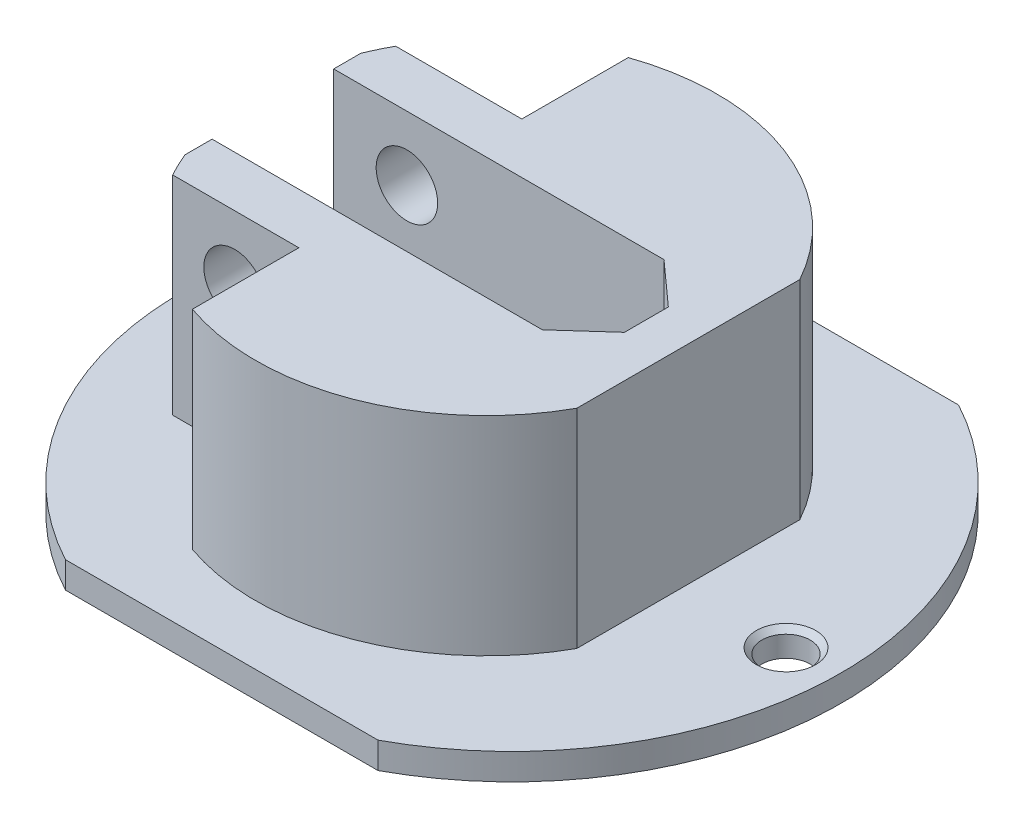
SolidWorks part; units mm, degrees
ref_plane "Front Plane" through (0, 0, 0) normal (0, 0, 1) x (1, 0, 0)
ref_plane "Top Plane" through (0, 0, 0) normal (0, 1, 0) x (1, 0, 0)
ref_plane "Right Plane" through (0, 0, 0) normal (1, 0, 0) x (0, 0, -1)
sketch "Sketch1" plane through (0, 0, 0) normal (0, 1, 0) x (1, 0, 0)
  line L0 (0, 0) -> (12.8, 0)
  line L1 (12.8, 0) -> (15.6935, -2.6)
  line L2 (15.6935, -2.6) -> (15.6935, -5.6)
  line L3 (15.6935, -5.6) -> (12.8, -8.2)
  line L4 (12.8, -8.2) -> (0, -8.2)
  line L5 (0, -8.2) -> (0, 0)
  dimension "D1" = 12.8
  dimension "D2" = 3.89
  dimension "D3" = 3
  dimension "D4" = 3.89
  dimension "D5" = 8.2
sketch "Sketch2" plane through (0, 0, 0) normal (0, 1, 0) x (1, 0, 0)
  line L9 (2.5617, 3.5098) -> (-4.4383, 3.5098)
  line L13 (-4.4383, -11.7098) -> (2.5617, -11.7098)
  line L21 (15.7777, 0.05) -> (-5.3065, 0.05)
  line L22 (0, 0) -> (12.8, 0) construction
  line L24 (15.7777, -8.25) -> (-5.3065, -8.25)
  line L25 (12.8, -8.2) -> (0, -8.2) construction
  line L27 (18.6713, -2.5999) -> (18.6713, -5.5999)
  line L28 (18.6713, -5.5999) -> (15.7777, -8.1998)
  line L30 (18.6713, -2.5999) -> (15.7777, 0)
  line L36 (2.5617, 3.5098) -> (2.5617, 9.296)
  line L37 (2.5617, -11.7098) -> (2.5617, -17.496)
  line L39 (15.7777, -8.1998) -> (15.7777, -8.25)
  line L40 (15.7777, 0.05) -> (15.7777, 0)
  line L41 (2.5617, 9.296) -> (2.5617, 10.7732)
  line L42 (-4.4383, 3.5098) -> (-6.0462, 3.5098)
  line L43 (-6.8189, 1.9) -> (-6.8189, 0.05)
  line L44 (-6.8189, 0.05) -> (-5.3065, 0.05)
  line L45 (2.5617, -17.496) -> (2.5617, -18.9732)
  line L46 (-4.4383, -11.7098) -> (-6.0462, -11.7098)
  line L47 (-6.8189, -10.1) -> (-6.8189, -8.25)
  line L48 (-6.8189, -8.25) -> (-5.3065, -8.25)
  line L49 (21.5331, 3.5098) -> (21.5331, -11.7098)
  arc A4 (-6.8189, -10.1) -> (-6.0462, -11.7098) centre (7.7435, -4.1) ccw
  arc A5 (2.5617, -18.9732) -> (21.5331, -11.7098) centre (7.7435, -4.1) ccw
  arc A6 (-6.0462, 3.5098) -> (-6.8189, 1.9) centre (7.7435, -4.1) ccw
  arc A7 (21.5331, 3.5098) -> (2.5617, 10.7732) centre (7.7435, -4.1) ccw
  dimension "D3" = 3
  dimension "D2" = 7
  dimension "D10" = 31.5
  dimension "D1" = 0.05
  dimension "D4" = 5.7862
  dimension "D5" = 2.8618
  dimension "D6" = 0.05
  dimension "D7" = 3.89
  dimension "D8" = 3.89
  dimension "D9" = 131.94
  dimension "D11" = 131.94
extrude "Boss-Extrude1" add sketch "Sketch2" along normal blind 16
sketch "Sketch4" plane through (0, 0, 0) normal (0, 1, 0) x (1, 0, 0)
  line L0 (0, -8.2) -> (0, 0) construction
  line L1 (0, 0) -> (12.8, 0) construction
  line L4 (-1.1675, 15.7105) -> (20.1675, 15.7105)
  line L5 (20.1675, -23.9105) -> (-1.1675, -23.9105)
  arc A2 (20.1675, -23.9105) -> (20.1675, 15.7105) centre (9.5, -4.1) ccw
  arc A3 (-1.1675, 15.7105) -> (-1.1675, -23.9105) centre (9.5, -4.1) ccw
  dimension "D3" = 45
  dimension "D1" = 9.5
  dimension "D2" = 4.1
  dimension "D4" = 21.335
  dimension "D5" = 21.335
extrude "Boss-Extrude2" add sketch "Sketch4" along normal blind 1.8
hole_wizard "M4 Tapped Hole1" positions "Sketch7" profile "Sketch8" tap size "M4" standard "ISO" end condition through all
sketch "Sketch7" plane through (0, 1.8, 0) normal (0, 1, 0) x (1, 0, 0)
  point P0 (28.6207, -4.5185)
  point P2 (-9.3855, -4.4692)
  point P5 (-9.3855, -4.4692)
  point P7 (-9.3855, -4.4692)
  point P13 (28.6207, -4.5185)
  point P22 (-9.3855, -4.4692)
  point P25 (28.6207, -4.5185)
sketch "Sketch8" plane through (28.6207, 1.8, 4.5185) normal (1, 0, 0) x (0, 0, 1)
  line L0 (0, 0) -> (0, 1.8)
  line L1 (0, 1.8) -> (1.65, 1.8)
  line L2 (1.65, 1.8) -> (1.65, 0.375)
  line L3 (1.65, 0.375) -> (2.025, 0)
  line L5 (2.025, 0) -> (0, 0)
  line L6 (-1.65, 0.375) -> (-2.025, 0) construction
  line L11 (0, -6.35) -> (0, 107.95) construction
  dimension "Thru Tap Drill Dia." = 3.3
  dimension "Thru Tap Drill Depth" = 1.8
  dimension "Near C'Sink Dia." = 4.05
  dimension "Near C'Sink Angle" = 90
cosmetic thread "Hole Thread2" parameters "D2"=4
cosmetic thread "Hole Thread4" parameters "D2"=4
cosmetic thread "Hole Thread6" parameters "D2"=4
cosmetic thread "Hole Thread8" parameters "D2"=4
cosmetic thread "Hole Thread9" parameters "D2"=4
cosmetic thread "Hole Thread10" parameters "D2"=4
cosmetic thread "Hole Thread11" parameters "D2"=4
ref_plane "Plane4" through (0, 0, -10.05) normal (0, 0, 1) x (1, 0, 0)
hole_wizard "M5 Tapped Hole1" positions "Sketch23" profile "Sketch24" tap size "M5" standard "ISO" end condition through all
sketch "Sketch23" plane through (0, 0, -10.05) normal (0, 0, 1) x (1, 0, 0)
  point P0 (-1.8238, 11.6162)
  point P3 (-1.8238, 11.6162)
  point P10 (-1.6246, 11.6162)
  point P11 (0, 0)
  point P12 (-1.8238, 11.6162)
sketch "Sketch24" plane through (-1.8238, 11.6162, -10.05) normal (1, 0, 0) x (0, 1, 0)
  line L0 (0, 0) -> (0, 33.9605)
  line L1 (0, 33.9605) -> (2.1, 33.9605)
  line L2 (2.1, 33.9605) -> (2.1, 0.425)
  line L3 (2.1, 0.425) -> (2.525, 0)
  line L5 (2.525, 0) -> (0, 0)
  line L6 (-2.1, 0.425) -> (-2.525, 0) construction
  line L11 (0, -6.35) -> (0, 107.95) construction
  dimension "Thru Tap Drill Dia." = 4.2
  dimension "Thru Tap Drill Depth" = 33.9605
  dimension "Near C'Sink Dia." = 5.05
  dimension "Near C'Sink Angle" = 90
cosmetic thread "Hole Thread12" parameters "D1"=21.7598, "D2"=5
cosmetic thread "Hole Thread13" parameters "D1"=21.7598, "D2"=5
sketch "Sketch25" plane through (0, 16, 0) normal (0, 1, 0) x (1, 0, 0)
  line L0 (15.7777, 0) -> (18.6713, -2.5999)
  line L1 (18.6713, -2.5999) -> (18.6713, -5.5999)
  line L8 (18.6713, -5.5999) -> (15.7777, -8.1998)
  line L9 (15.7777, -8.1998) -> (15.7777, -8.25)
  line L11 (15.7777, -8.25) -> (-6.8189, -8.25) construction
  line L13 (-6.8189, 0.05) -> (15.7777, 0.05) construction
  line L15 (15.7777, 0.05) -> (15.7777, 0)
  line L16 (15.7777, -8.25) -> (2.8213, -8.25)
  line L17 (2.8213, 0.05) -> (15.7777, 0.05)
  line L18 (2.8213, 0.05) -> (2.8213, -8.25)
  dimension "D1" = 15.85
  dimension "D2" = 3.89
extrude "Cut-Extrude1" cut sketch "Sketch25" against normal up to next
